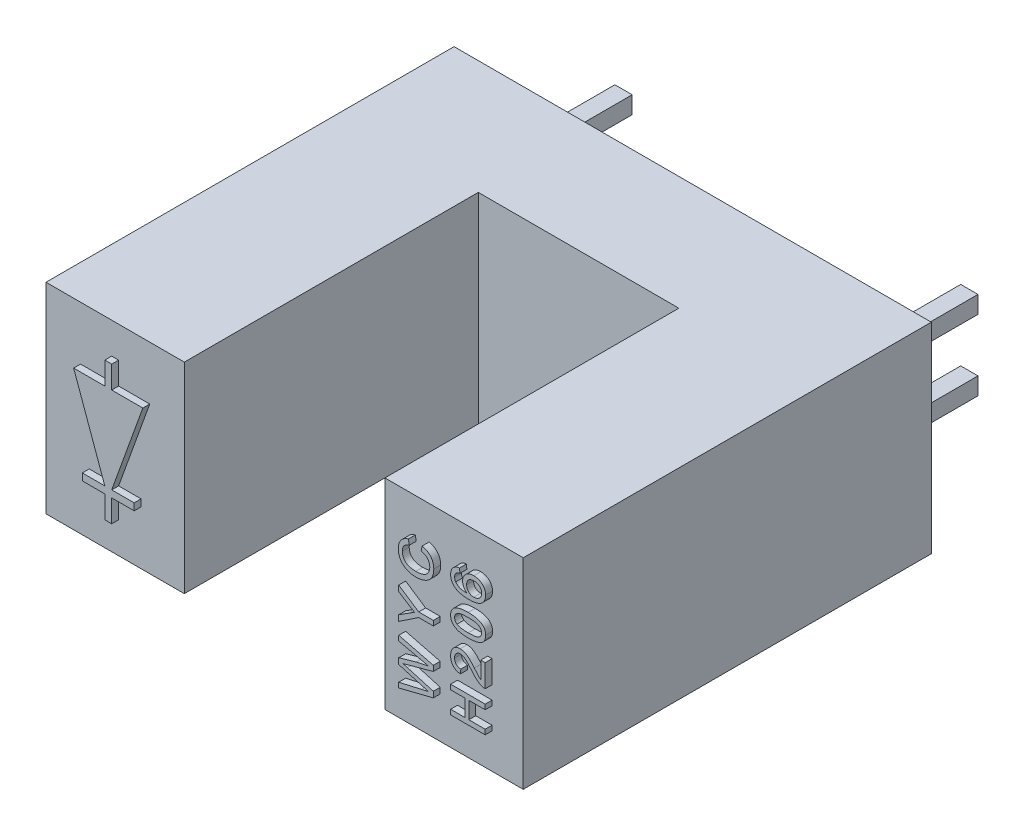
SolidWorks part; units mm, degrees
ref_plane "Front Plane" through (0, 0, 0) normal (0, 0, 1) x (1, 0, 0)
ref_plane "Top Plane" through (0, 0, 0) normal (0, 1, 0) x (1, 0, 0)
ref_plane "Right Plane" through (0, 0, 0) normal (1, 0, 0) x (0, 0, -1)
sketch "Sketch1" plane through (0, 0, 0) normal (0, 0, 1) x (1, 0, 0)
  line L1 (-6.9, 2.9) -> (6.9, 2.9)
  line L2 (-6.9, 2.9) -> (-6.9, -2.9)
  line L3 (-6.9, -2.9) -> (6.9, -2.9)
  line L4 (6.9, 2.9) -> (6.9, -2.9)
  line L5 (-6.9, 2.9) -> (6.9, -2.9) construction
  line L6 (-6.9, -2.9) -> (6.9, 2.9) construction
  point P0 (0, 0)
  dimension "D1" = 13.8
  dimension "D2" = 5.8
extrude "Boss-Extrude1" add sketch "Sketch1" along normal blind 11.8
sketch "Sketch2" plane through (0, -2.9, 0) normal (0, -1, 0) x (1, 0, 0)
  line L0 (-6.9, 11.8) -> (6.9, 11.8) construction
  line L1 (-2.9, 11.8) -> (2.9, 11.8)
  line L2 (-2.9, 11.8) -> (-2.9, 3.3)
  line L3 (-2.9, 3.3) -> (2.9, 3.3)
  line L4 (2.9, 11.8) -> (2.9, 3.3)
  line L5 (-6.9, 11.8) -> (-6.9, 0) construction
  line L6 (6.9, 11.8) -> (6.9, 0) construction
  line L7 (-6.9, 0) -> (6.9, 0) construction
  dimension "D1" = 4
  dimension "D2" = 4
  dimension "D3" = 3.3
extrude "Cut-Extrude1" cut sketch "Sketch2" against normal blind 11.8 contours L1 L4 L3 L2
sketch "Sketch3" plane through (0, 0, 11.8) normal (0, 0, 1) x (1, 0, 0)
  line L0 (-6.9, 2.9) -> (-6.9, -2.9) construction
  line L1 (-5, 2) -> (-4.8, 2)
  line L2 (-5, 2) -> (-5, 1.35)
  line L3 (-5, -2) -> (-4.8, -2)
  line L4 (-4.8, 2) -> (-4.8, 1.35)
  line L5 (-5.65, -1.15) -> (-5, -1.15)
  line L6 (-5.65, -1.15) -> (-5.65, -1.35)
  line L7 (-5.65, -1.35) -> (-5, -1.35)
  line L8 (-4.15, -1.15) -> (-4.15, -1.35)
  line L9 (-2.9, 2.9) -> (-6.9, 2.9) construction
  line L11 (-4.8, -1.15) -> (-4.15, -1.15)
  line L12 (-5, -1.35) -> (-5, -2)
  line L13 (-4.8, -1.35) -> (-4.15, -1.35)
  line L14 (-4.8, -1.35) -> (-4.8, -2)
  line L15 (-5, -1.15) -> (-5.9, 1.35)
  line L16 (-5.9, 1.35) -> (-5, 1.35)
  line L17 (-3.9, 1.35) -> (-4.8, -1.15)
  line L18 (-4.8, 1.35) -> (-3.9, 1.35)
  line L19 (4.5, 2) -> (4.5, -2) construction
  line L20 (6, 2) -> (6, -2) construction
  line L21 (2.9, -2.9) -> (6.9, -2.9) construction
  line L22 (2.9, 2.9) -> (2.9, -2.9) construction
  text T0 "WYC" font "Arial" height 1
  text T1 "H206" font "Arial" height 1
  dimension "D1" = 0.2
  dimension "D2" = 0.2
  dimension "D3" = 1.5
  dimension "D4" = 0.65
  dimension "D5" = 0.65
  dimension "D6" = 1.25
  dimension "D7" = 4
  dimension "D8" = 0.9
  dimension "D9" = 0.65
  dimension "D10" = 2
  dimension "D11" = 0.9
  dimension "D12" = 4
  dimension "D13" = 0.9
  dimension "D14" = 1.6
  dimension "D15" = 4
  dimension "D16" = 0.9
  dimension "D17" = 1.5
extrude "Boss-Extrude3" add sketch "Sketch3" along normal blind 0.2
sketch "Sketch4" plane through (0, 0, 0) normal (0, 0, -1) x (-1, 0, 0)
  line L0 (4.75, 1.27) -> (5.25, 1.27)
  line L1 (-5.25, 1.27) -> (-4.75, 1.27)
  line L2 (-5.25, 1.27) -> (-5.25, 0.77)
  line L3 (-5.25, 0.77) -> (-4.75, 0.77)
  line L4 (-4.75, 1.27) -> (-4.75, 0.77)
  line L5 (-5.25, 1.27) -> (-4.75, 0.77) construction
  line L6 (-5.25, 0.77) -> (-4.75, 1.27) construction
  line L7 (-5.25, -0.77) -> (-4.75, -0.77)
  line L8 (-5.25, -0.77) -> (-5.25, -1.27)
  line L9 (-5.25, -1.27) -> (-4.75, -1.27)
  line L10 (-4.75, -0.77) -> (-4.75, -1.27)
  line L11 (-5.25, -0.77) -> (-4.75, -1.27) construction
  line L12 (-5.25, -1.27) -> (-4.75, -0.77) construction
  line L13 (4.75, 1.27) -> (4.75, 0.77)
  line L14 (4.75, 0.77) -> (5.25, 0.77)
  line L15 (5.25, 1.27) -> (5.25, 0.77)
  line L16 (4.75, -0.77) -> (5.25, -0.77)
  line L17 (4.75, -0.77) -> (4.75, -1.27)
  line L18 (4.75, -1.27) -> (5.25, -1.27)
  line L19 (5.25, -0.77) -> (5.25, -1.27)
  line L20 (4.75, 1.27) -> (5.25, 0.77) construction
  line L21 (4.75, 0.77) -> (5.25, 1.27) construction
  line L22 (4.75, -0.77) -> (5.25, -1.27) construction
  line L23 (4.75, -1.27) -> (5.25, -0.77) construction
  point P0 (-5, 1.02)
  point P5 (-5, -1.02)
  point P13 (5, 1.02)
  point P18 (5, -1.02)
  dimension "D1" = 2.04
  dimension "D2" = 1.02
  dimension "D3" = 0.5
  dimension "D4" = 0.5
  dimension "D5" = 0.5
  dimension "D6" = 0.5
  dimension "D7" = 5
  dimension "D8" = 2
extrude "Boss-Extrude4" add sketch "Sketch4" along normal blind 3
